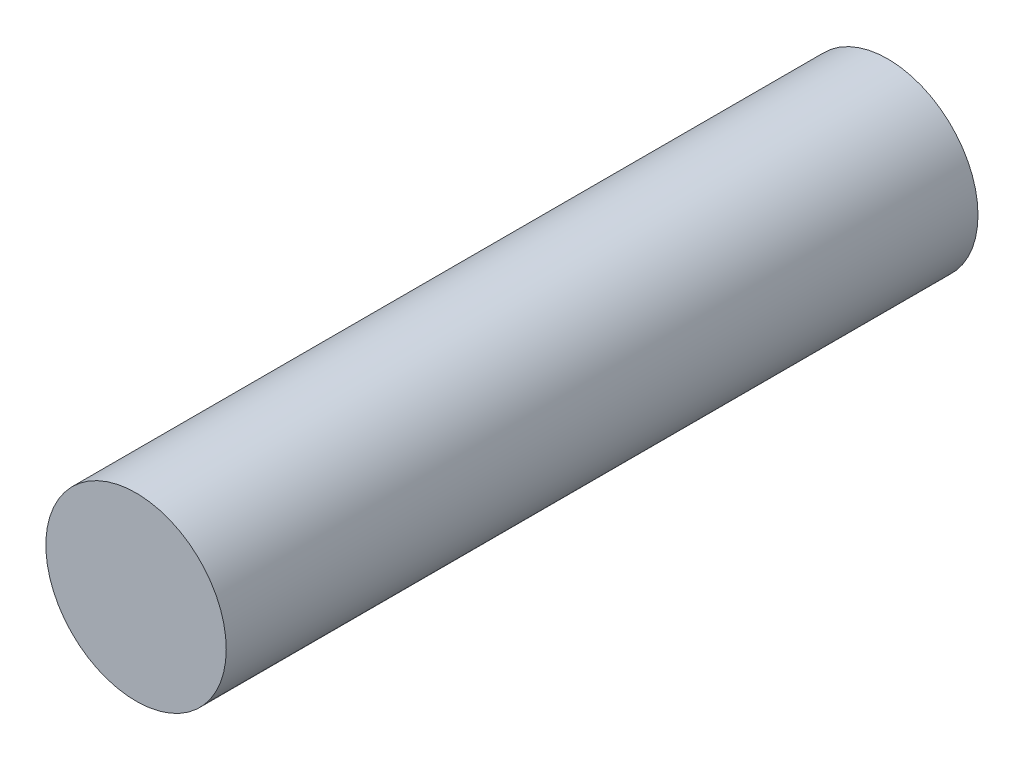
SolidWorks part; units mm, degrees
ref_plane "Front Plane" through (0, 0, 0) normal (0, 0, 1) x (1, 0, 0)
ref_plane "Top Plane" through (0, 0, 0) normal (0, 1, 0) x (1, 0, 0)
ref_plane "Right Plane" through (0, 0, 0) normal (1, 0, 0) x (0, 0, -1)
sketch "Sketch1" plane through (0, 0, 0) normal (0, 0, 1) x (1, 0, 0)
  circle A0 centre (0, 0) radius 1.8
  dimension "D1" = 3.6
extrude "Boss-Extrude1" add sketch "Sketch1" along normal blind 15
